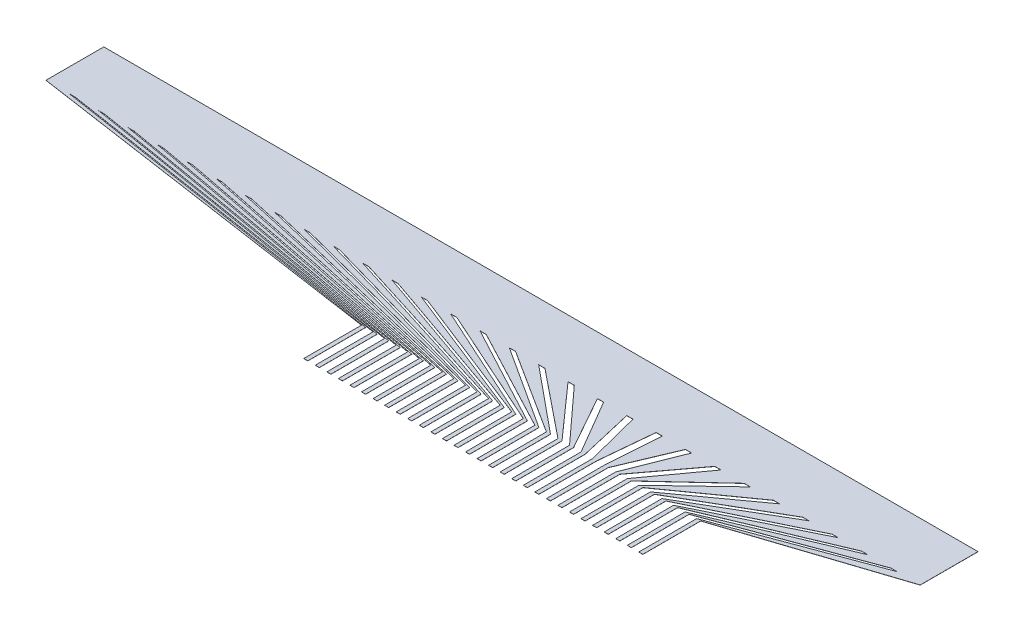
SolidWorks part; units mm, degrees
ref_plane "前视基准面" through (0, 0, 0) normal (0, 0, 1) x (1, 0, 0)
ref_plane "上视基准面" through (0, 0, 0) normal (0, 1, 0) x (1, 0, 0)
ref_plane "右视基准面" through (0, 0, 0) normal (1, 0, 0) x (0, 0, -1)
sketch "草图1" plane through (0, 0, 0) normal (0, 1, 0) x (1, 0, 0)
  line L0 (0, 0) -> (76.2, 0) construction
  line L1 (0, 0) -> (0, -25.4) construction
  line L2 (0, -25.4) -> (76.2, -25.4) construction
  line L3 (76.2, -25.4) -> (76.2, 0) construction
  line L4 (0, -12.7) -> (76.2, -12.7) construction
  line L5 (76.2, 0) -> (76.2, -5)
  line L7 (74.2, -5) -> (74.2, 0)
  line L8 (74.2, 0) -> (76.2, 0)
  line L9 (71.66, 0) -> (73.66, 0)
  line L10 (73.66, 0) -> (73.66, -5)
  line L12 (71.66, -5) -> (71.66, 0)
  line L13 (69.12, 0) -> (71.12, 0)
  line L14 (71.12, 0) -> (71.12, -5)
  line L16 (69.12, -5) -> (69.12, 0)
  line L17 (66.58, 0) -> (68.58, 0)
  line L18 (68.58, 0) -> (68.58, -5)
  line L20 (66.58, -5) -> (66.58, 0)
  line L21 (64.04, 0) -> (66.04, 0)
  line L22 (66.04, 0) -> (66.04, -5)
  line L24 (64.04, -5) -> (64.04, 0)
  line L25 (61.5, 0) -> (63.5, 0)
  line L26 (63.5, 0) -> (63.5, -5)
  line L28 (61.5, -5) -> (61.5, 0)
  line L29 (58.96, 0) -> (60.96, 0)
  line L30 (60.96, 0) -> (60.96, -5)
  line L32 (58.96, -5) -> (58.96, 0)
  line L33 (56.42, 0) -> (58.42, 0)
  line L34 (58.42, 0) -> (58.42, -5)
  line L36 (56.42, -5) -> (56.42, 0)
  line L37 (53.88, 0) -> (55.88, 0)
  line L38 (55.88, 0) -> (55.88, -5)
  line L40 (53.88, -5) -> (53.88, 0)
  line L41 (51.34, 0) -> (53.34, 0)
  line L42 (53.34, 0) -> (53.34, -5)
  line L44 (51.34, -5) -> (51.34, 0)
  line L45 (48.8, 0) -> (50.8, 0)
  line L46 (50.8, 0) -> (50.8, -5)
  line L48 (48.8, -5) -> (48.8, 0)
  line L49 (46.26, 0) -> (48.26, 0)
  line L50 (48.26, 0) -> (48.26, -5)
  line L52 (46.26, -5) -> (46.26, 0)
  line L53 (43.72, 0) -> (45.72, 0)
  line L54 (45.72, 0) -> (45.72, -5)
  line L56 (43.72, -5) -> (43.72, 0)
  line L57 (41.18, 0) -> (43.18, 0)
  line L58 (43.18, 0) -> (43.18, -5)
  line L60 (41.18, -5) -> (41.18, 0)
  line L61 (38.64, 0) -> (40.64, 0)
  line L62 (40.64, 0) -> (40.64, -5)
  line L64 (38.64, -5) -> (38.64, 0)
  line L65 (36.1, 0) -> (38.1, 0)
  line L66 (38.1, 0) -> (38.1, -5)
  line L68 (36.1, -5) -> (36.1, 0)
  line L69 (33.56, 0) -> (35.56, 0)
  line L70 (35.56, 0) -> (35.56, -5)
  line L72 (33.56, -5) -> (33.56, 0)
  line L73 (31.02, 0) -> (33.02, 0)
  line L74 (33.02, 0) -> (33.02, -5)
  line L76 (31.02, -5) -> (31.02, 0)
  line L77 (28.48, 0) -> (30.48, 0)
  line L78 (30.48, 0) -> (30.48, -5)
  line L80 (28.48, -5) -> (28.48, 0)
  line L81 (25.94, 0) -> (27.94, 0)
  line L82 (27.94, 0) -> (27.94, -5)
  line L84 (25.94, -5) -> (25.94, 0)
  line L85 (23.4, 0) -> (25.4, 0)
  line L86 (25.4, 0) -> (25.4, -5)
  line L88 (23.4, -5) -> (23.4, 0)
  line L89 (20.86, 0) -> (22.86, 0)
  line L90 (22.86, 0) -> (22.86, -5)
  line L92 (20.86, -5) -> (20.86, 0)
  line L93 (18.32, 0) -> (20.32, 0)
  line L94 (20.32, 0) -> (20.32, -5)
  line L96 (18.32, -5) -> (18.32, 0)
  line L97 (15.78, 0) -> (17.78, 0)
  line L98 (17.78, 0) -> (17.78, -5)
  line L100 (15.78, -5) -> (15.78, 0)
  line L101 (13.24, 0) -> (15.24, 0)
  line L102 (15.24, 0) -> (15.24, -5)
  line L104 (13.24, -5) -> (13.24, 0)
  line L105 (10.7, 0) -> (12.7, 0)
  line L106 (12.7, 0) -> (12.7, -5)
  line L108 (10.7, -5) -> (10.7, 0)
  line L109 (8.16, 0) -> (10.16, 0)
  line L110 (10.16, 0) -> (10.16, -5)
  line L112 (8.16, -5) -> (8.16, 0)
  line L113 (5.62, 0) -> (7.62, 0)
  line L114 (7.62, 0) -> (7.62, -5)
  line L116 (5.62, -5) -> (5.62, 0)
  line L117 (3.08, 0) -> (5.08, 0)
  line L118 (5.08, 0) -> (5.08, -5)
  line L120 (3.08, -5) -> (3.08, 0)
  line L121 (0.54, 0) -> (2.54, 0)
  line L122 (2.54, 0) -> (2.54, -5)
  line L124 (0.54, -5) -> (0.54, 0)
  line L361 (61.8976, -15.7) -> (61.8976, -9.7)
  line L362 (61.55, -9.7) -> (61.8976, -9.7) construction
  line L363 (61.55, -9.7) -> (61.55, -15.7)
  line L365 (60.8976, -15.7) -> (60.8976, -9.7)
  line L367 (60.55, -9.7) -> (60.55, -15.7)
  line L368 (59.8976, -15.7) -> (59.8976, -9.7)
  line L370 (59.55, -9.7) -> (59.55, -15.7)
  line L371 (58.8976, -15.7) -> (58.8976, -9.7)
  line L373 (58.55, -9.7) -> (58.55, -15.7)
  line L374 (57.8976, -15.7) -> (57.8976, -9.7)
  line L376 (57.55, -9.7) -> (57.55, -15.7)
  line L377 (56.8976, -15.7) -> (56.8976, -9.7)
  line L379 (56.55, -9.7) -> (56.55, -15.7)
  line L380 (55.8976, -15.7) -> (55.8976, -9.7)
  line L382 (55.55, -9.7) -> (55.55, -15.7)
  line L383 (54.8976, -15.7) -> (54.8976, -9.7)
  line L385 (54.55, -9.7) -> (54.55, -15.7)
  line L386 (53.8976, -15.7) -> (53.8976, -9.7)
  line L388 (53.55, -9.7) -> (53.55, -15.7)
  line L389 (52.8976, -15.7) -> (52.8976, -9.7)
  line L391 (52.55, -9.7) -> (52.55, -15.7)
  line L392 (51.8976, -15.7) -> (51.8976, -9.7)
  line L394 (51.55, -9.7) -> (51.55, -15.7)
  line L395 (50.8976, -15.7) -> (50.8976, -9.7)
  line L397 (50.55, -9.7) -> (50.55, -15.7)
  line L398 (49.8976, -15.7) -> (49.8976, -9.7)
  line L400 (49.55, -9.7) -> (49.55, -15.7)
  line L401 (48.8976, -15.7) -> (48.8976, -9.7)
  line L403 (48.55, -9.7) -> (48.55, -15.7)
  line L404 (47.8976, -15.7) -> (47.8976, -9.7)
  line L406 (47.55, -9.7) -> (47.55, -15.7)
  line L407 (46.8976, -15.7) -> (46.8976, -9.7)
  line L409 (46.55, -9.7) -> (46.55, -15.7)
  line L410 (45.8976, -15.7) -> (45.8976, -9.7)
  line L412 (45.55, -9.7) -> (45.55, -15.7)
  line L413 (44.8976, -15.7) -> (44.8976, -9.7)
  line L415 (44.55, -9.7) -> (44.55, -15.7)
  line L416 (43.8976, -15.7) -> (43.8976, -9.7)
  line L418 (43.55, -9.7) -> (43.55, -15.7)
  line L419 (42.8976, -15.7) -> (42.8976, -9.7)
  line L421 (42.55, -9.7) -> (42.55, -15.7)
  line L422 (41.8976, -15.7) -> (41.8976, -9.7)
  line L424 (41.55, -9.7) -> (41.55, -15.7)
  line L425 (40.8976, -15.7) -> (40.8976, -9.7)
  line L427 (40.55, -9.7) -> (40.55, -15.7)
  line L428 (39.8976, -15.7) -> (39.8976, -9.7)
  line L430 (39.55, -9.7) -> (39.55, -15.7)
  line L431 (38.8976, -15.7) -> (38.8976, -9.7)
  line L433 (38.55, -9.7) -> (38.55, -15.7)
  line L434 (37.8976, -15.7) -> (37.8976, -9.7)
  line L436 (37.55, -9.7) -> (37.55, -15.7)
  line L437 (36.8976, -15.7) -> (36.8976, -9.7)
  line L439 (36.55, -9.7) -> (36.55, -15.7)
  line L440 (35.8976, -15.7) -> (35.8976, -9.7)
  line L442 (35.55, -9.7) -> (35.55, -15.7)
  line L443 (34.8976, -15.7) -> (34.8976, -9.7)
  line L445 (34.55, -9.7) -> (34.55, -15.7)
  line L446 (33.8976, -15.7) -> (33.8976, -9.7)
  line L448 (33.55, -9.7) -> (33.55, -15.7)
  line L449 (32.8976, -15.7) -> (32.8976, -9.7)
  line L451 (32.55, -9.7) -> (32.55, -15.7)
  line L452 (74.2, -5) -> (61.55, -9.7)
  line L453 (61.8976, -9.7) -> (76.2, -5)
  line L454 (73.66, -5) -> (60.8976, -9.7)
  line L455 (60.55, -9.7) -> (71.66, -5)
  line L456 (71.12, -5) -> (59.8976, -9.7)
  line L457 (59.55, -9.7) -> (69.12, -5)
  line L458 (68.58, -5) -> (58.8976, -9.7)
  line L459 (66.58, -5) -> (58.55, -9.7)
  line L460 (57.8976, -9.7) -> (66.04, -5)
  line L461 (64.04, -5) -> (57.55, -9.7)
  line L462 (56.8976, -9.7) -> (63.5, -5)
  line L463 (61.5, -5) -> (56.55, -9.7)
  line L464 (58.96, -5) -> (55.55, -9.7)
  line L465 (60.96, -5) -> (55.8976, -9.7)
  line L466 (54.8976, -9.7) -> (58.42, -5)
  line L467 (54.55, -9.7) -> (56.42, -5)
  line L468 (55.88, -5) -> (53.8976, -9.7)
  line L469 (53.55, -9.7) -> (53.88, -5)
  line L470 (53.34, -5) -> (52.8976, -9.7)
  line L471 (52.55, -9.7) -> (51.34, -5)
  line L472 (50.8, -5) -> (51.8976, -9.7)
  line L473 (51.55, -9.7) -> (48.8, -5)
  line L474 (48.26, -5) -> (50.8976, -9.7)
  line L475 (50.55, -9.7) -> (46.26, -5)
  line L476 (45.72, -5) -> (49.8976, -9.7)
  line L477 (49.55, -9.7) -> (43.72, -5)
  line L478 (48.8976, -9.7) -> (43.18, -5)
  line L479 (41.18, -5) -> (48.55, -9.7)
  line L480 (47.8976, -9.7) -> (40.64, -5)
  line L481 (38.64, -5) -> (47.55, -9.7)
  line L482 (46.8976, -9.7) -> (38.1, -5)
  line L483 (36.1, -5) -> (46.55, -9.7)
  line L484 (45.8976, -9.7) -> (35.56, -5)
  line L485 (33.56, -5) -> (45.55, -9.7)
  line L486 (33.02, -5) -> (44.8976, -9.7)
  line L487 (44.55, -9.7) -> (31.02, -5)
  line L488 (30.48, -5) -> (43.8976, -9.7)
  line L489 (43.55, -9.7) -> (28.48, -5)
  line L490 (27.94, -5) -> (42.8976, -9.7)
  line L491 (42.55, -9.7) -> (25.94, -5)
  line L492 (25.4, -5) -> (41.8976, -9.7)
  line L493 (41.55, -9.7) -> (23.4, -5)
  line L494 (22.86, -5) -> (40.8976, -9.7)
  line L495 (40.55, -9.7) -> (20.86, -5)
  line L496 (20.32, -5) -> (39.8976, -9.7)
  line L497 (39.55, -9.7) -> (18.32, -5)
  line L498 (17.78, -5) -> (38.8976, -9.7)
  line L499 (38.55, -9.7) -> (15.78, -5)
  line L500 (15.24, -5) -> (37.8976, -9.7)
  line L501 (37.55, -9.7) -> (13.24, -5)
  line L502 (12.7, -5) -> (36.8976, -9.7)
  line L503 (36.55, -9.7) -> (10.7, -5)
  line L504 (10.16, -5) -> (35.8976, -9.7)
  line L505 (35.55, -9.7) -> (8.16, -5)
  line L506 (7.62, -5) -> (34.8976, -9.7)
  line L507 (34.55, -9.7) -> (5.62, -5)
  line L508 (5.08, -5) -> (33.8976, -9.7)
  line L509 (33.55, -9.7) -> (3.08, -5)
  line L510 (2.54, -5) -> (32.8976, -9.7)
  line L511 (32.55, -9.7) -> (0.54, -5)
  line L512 (32.55, -15.7) -> (32.8976, -15.7)
  line L513 (33.55, -15.7) -> (33.8976, -15.7)
  line L514 (34.55, -15.7) -> (34.8976, -15.7)
  line L515 (35.55, -15.7) -> (35.8976, -15.7)
  line L516 (36.55, -15.7) -> (36.8976, -15.7)
  line L517 (37.55, -15.7) -> (37.8976, -15.7)
  line L518 (38.55, -15.7) -> (38.8976, -15.7)
  line L519 (39.55, -15.7) -> (39.8976, -15.7)
  line L520 (40.55, -15.7) -> (40.8976, -15.7)
  line L521 (41.55, -15.7) -> (41.8976, -15.7)
  line L522 (42.55, -15.7) -> (42.8976, -15.7)
  line L523 (43.55, -15.7) -> (43.8976, -15.7)
  line L524 (44.55, -15.7) -> (44.8976, -15.7)
  line L525 (45.55, -15.7) -> (45.8976, -15.7)
  line L526 (46.55, -15.7) -> (46.8976, -15.7)
  line L527 (47.55, -15.7) -> (47.8976, -15.7)
  line L528 (48.55, -15.7) -> (48.8976, -15.7)
  line L529 (49.55, -15.7) -> (49.8976, -15.7)
  line L530 (50.55, -15.7) -> (50.8976, -15.7)
  line L531 (51.55, -15.7) -> (51.8976, -15.7)
  line L532 (52.55, -15.7) -> (52.8976, -15.7)
  line L533 (53.55, -15.7) -> (53.8976, -15.7)
  line L534 (54.55, -15.7) -> (54.8976, -15.7)
  line L535 (55.55, -15.7) -> (55.8976, -15.7)
  line L536 (56.55, -15.7) -> (56.8976, -15.7)
  line L537 (57.55, -15.7) -> (57.8976, -15.7)
  line L538 (58.55, -15.7) -> (58.8976, -15.7)
  line L539 (59.55, -15.7) -> (59.8976, -15.7)
  line L540 (60.55, -15.7) -> (60.8976, -15.7)
  line L541 (61.55, -15.7) -> (61.8976, -15.7)
  line L543 (62.55, -15.7) -> (62.8976, -15.7) [skipped]
  dimension "D1" = 30
  dimension "D2" = 30
  dimension "D3" = 31
extrude "凸台-拉伸1" add sketch "草图1" along normal blind 0.01
sketch "草图2" plane through (0, 0.01, 0) normal (0, 1, 0) x (1, 0, 0)
  line L0 (0.54, 0) -> (76.2, 0)
  line L1 (76.2, 0) -> (76.2, -5)
  line L2 (76.2, -5) -> (0.54, -5)
  line L3 (0.54, -5) -> (0.54, 0)
extrude "凸台-拉伸2" add sketch "草图2" against normal up to surface (0.01 mm away) up to face at (22.4419, 0, 7.6)
sketch "草图3" plane through (0, 0.01, 0) normal (0, 1, 0) x (1, 0, 0)
  line L0 (32.55, -15.7) -> (32.55, -14.7)
  line L1 (32.55, -9.7) -> (32.55, -15.7) construction
  line L2 (32.55, -14.7) -> (61.8976, -14.7)
  line L3 (61.8976, -15.7) -> (61.8976, -9.7) construction
  line L4 (61.8976, -14.7) -> (61.8976, -15.7)
  line L5 (61.8976, -15.7) -> (32.55, -15.7)
extrude "切除-拉伸1" cut sketch "草图3" against normal blind 0.01
